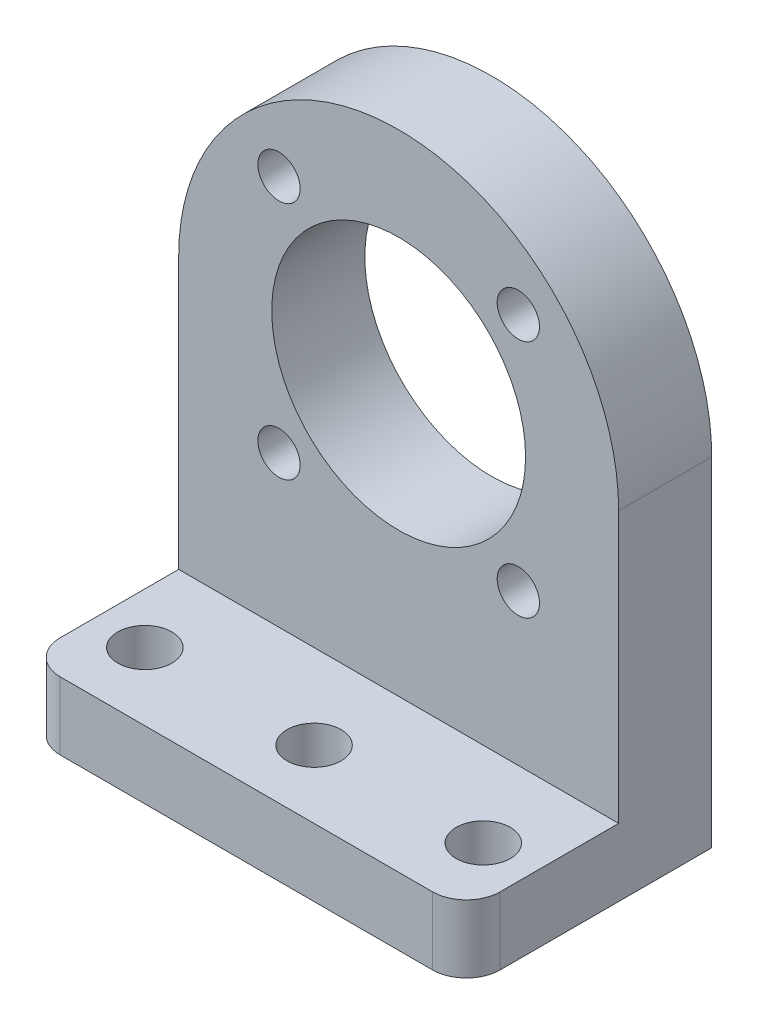
SolidWorks part; units mm, degrees
material "6061 合金"
ref_plane "前视基准面" through (0, 0, 0) normal (0, 0, 1) x (1, 0, 0)
ref_plane "上视基准面" through (0, 0, 0) normal (0, 1, 0) x (1, 0, 0)
ref_plane "右视基准面" through (0, 0, 0) normal (1, 0, 0) x (0, 0, -1)
other "Configuration Table"
sketch "草图1" plane through (0, 0, 0) normal (0, 0, 1) x (1, 0, 0)
  line L0 (-7.0711, 7.0711) -> (0, 0) construction
  line L1 (0, 0) -> (-7.5, 0) construction
  line L2 (-13, 0) -> (-13, -20)
  line L3 (-13, -20) -> (13, -20)
  line L4 (13, -20) -> (13, 0)
  circle A0 centre (0, 0) radius 7.5
  arc A1 (13, 0) -> (-13, 0) centre (0, 0) ccw
  circle A2 centre (-7.0711, 7.0711) radius 1.25
  circle A3 centre (7.0711, 7.0711) radius 1.25
  circle A4 centre (7.0711, -7.0711) radius 1.25
  circle A5 centre (-7.0711, -7.0711) radius 1.25
  point P20 (0, 0)
  dimension "D1" = 15
  dimension "D2" = 26
  dimension "D3" = 2.5
  dimension "D4" = 10
  dimension "D5" = 45
  dimension "D7" = 20
  dimension "D6" = 4
extrude "凸台-拉伸1" add sketch "草图1" along normal blind 5.5
cosmetic thread "装饰螺纹线1" parameters "D2"=3
cosmetic thread "装饰螺纹线2" parameters "D2"=3
cosmetic thread "装饰螺纹线3" parameters "D2"=3
cosmetic thread "装饰螺纹线4" parameters "D2"=3
sketch "草图2" plane through (0, 0, 5.5) normal (0, 0, 1) x (1, 0, 0)
  line L0 (-13, 0) -> (-13, -20) construction
  line L1 (-13, -16) -> (13, -16)
  line L2 (-13, -16) -> (-13, -20)
  line L3 (-13, -20) -> (13, -20)
  line L4 (13, -16) -> (13, -20)
  dimension "D1" = 4
extrude "凸台-拉伸2" add sketch "草图2" along normal blind 9
sketch "草图3" plane through (0, -16, 0) normal (0, 1, 0) x (1, 0, 0)
  line L0 (-13, -14.5) -> (-13, -5.5) construction
  line L1 (13, -14.5) -> (-13, -14.5) construction
  line L2 (-10, -10.5) -> (0, -10.5) construction
  circle A0 centre (-10, -10.5) radius 1.6
  circle A1 centre (0, -10.5) radius 1.6
  circle A2 centre (10, -10.5) radius 1.6
  dimension "D1" = 3.2
  dimension "D2" = 3
  dimension "D3" = 4
  dimension "D5" = 10
  dimension "D4" = 3
extrude "切除-拉伸1" cut sketch "草图3" against normal blind 12
fillet "圆角1" radius 2 2 edges at (13, -18, 14.5) (-13, -18, 14.5)
